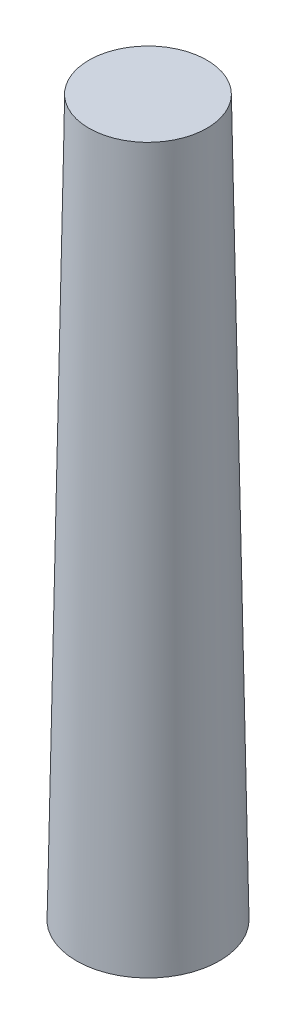
SolidWorks part; units mm, degrees
ref_plane "Front Plane" through (0, 0, 0) normal (0, 0, 1) x (1, 0, 0)
ref_plane "Top Plane" through (0, 0, 0) normal (0, 1, 0) x (1, 0, 0)
ref_plane "Right Plane" through (0, 0, 0) normal (1, 0, 0) x (0, 0, -1)
sketch "Sketch1" plane through (0, 0, 0) normal (0, 1, 0) x (1, 0, 0)
  circle A0 centre (0, 0) radius 1
extrude "Boss-Extrude1" add sketch "Sketch1" along normal blind 10 draft 1
